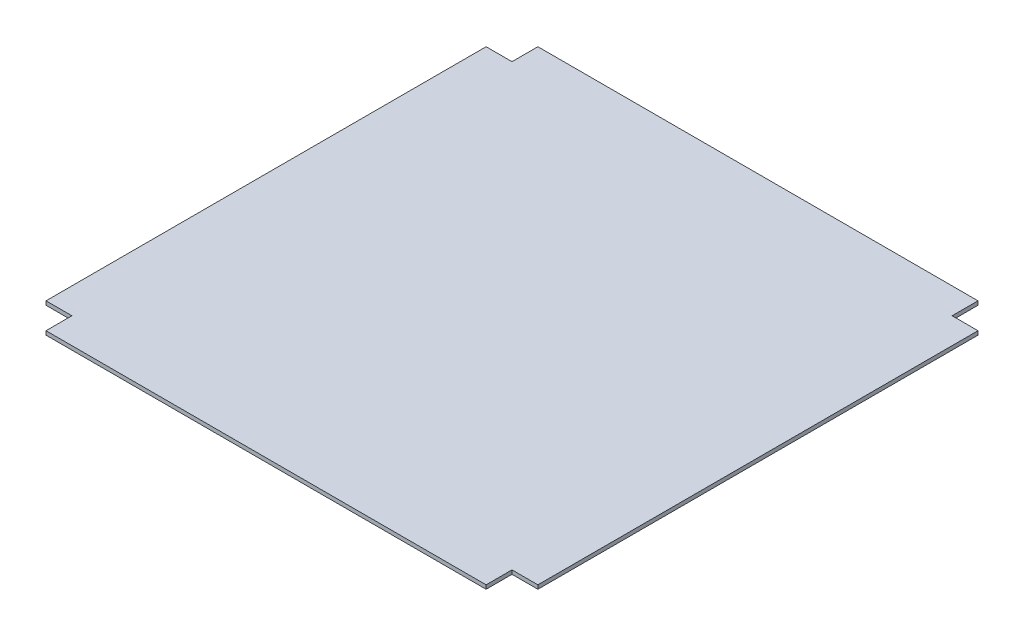
SolidWorks part; units mm, degrees
ref_plane "前视基准面" through (0, 0, 0) normal (0, 0, 1) x (1, 0, 0)
ref_plane "上视基准面" through (0, 0, 0) normal (0, 1, 0) x (1, 0, 0)
ref_plane "右视基准面" through (0, 0, 0) normal (1, 0, 0) x (0, 0, -1)
sketch "草图3" plane through (0, 0, 0) normal (0, 1, 0) x (1, 0, 0)
  line L0 (170, 190) -> (170, 170)
  line L1 (-170, 190) -> (170, 190)
  line L2 (-190, 170) -> (-190, -170)
  line L3 (-170, -190) -> (170, -190)
  line L4 (190, 170) -> (190, -170)
  line L5 (-170, 170) -> (170, -170) construction
  line L6 (-170, -170) -> (170, 170) construction
  line L7 (170, 170) -> (190, 170)
  line L8 (170, -170) -> (170, -190)
  line L9 (190, -170) -> (170, -170)
  line L10 (-170, -170) -> (-190, -170)
  line L11 (-170, -190) -> (-170, -170)
  line L12 (-170, 170) -> (-170, 190)
  line L13 (-190, 170) -> (-170, 170)
  point P0 (0, 0)
  point P20 (0, 0)
  dimension "D2" = 20
  dimension "D3" = 4
extrude "凸台-拉伸3" add sketch "草图3" along normal blind 3
sketch "草图4" plane through (0, 0, 0) normal (0, -1, 0) x (1, 0, 0)
  circle A0 centre (0, 0) radius 15
  dimension "D1" = 30
extrude "凸台-拉伸4" add sketch "草图4" along normal blind 1
